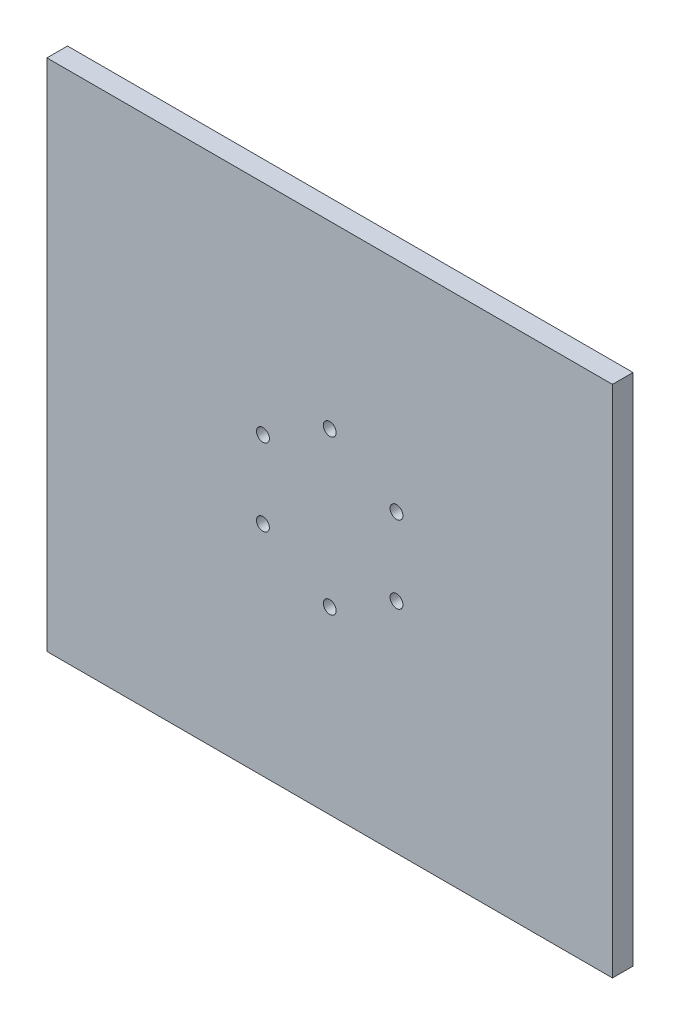
SolidWorks part; units mm, degrees
material "轻木"
ref_plane "前视基准面" through (0, 0, 0) normal (0, 0, 1) x (1, 0, 0)
ref_plane "上视基准面" through (0, 0, 0) normal (0, 1, 0) x (1, 0, 0)
ref_plane "右视基准面" through (0, 0, 0) normal (1, 0, 0) x (0, 0, -1)
sketch "草图1" plane through (0, 0, 0) normal (0, 0, 1) x (1, 0, 0)
  line L1 (0, 0) -> (220, 0)
  line L2 (0, 0) -> (0, -200)
  line L3 (0, -200) -> (220, -200)
  line L4 (220, 0) -> (220, -200)
  dimension "D1" = 200
  dimension "D2" = 220
extrude "凸台-拉伸1" add sketch "草图1" along normal blind 8
sketch "草图2" plane through (0, 0, 8) normal (0, 0, 1) x (1, 0, 0)
  line L0 (220, -200) -> (0, 0) construction
  line L1 (110, -100) -> (110, -70) construction
  line L2 (0, -200) -> (220, 0) construction
  circle A0 centre (110, -70) radius 2.5
  circle A1 centre (110, -100) radius 30 construction
  circle A2 centre (135.9808, -85) radius 2.5
  circle A3 centre (135.9808, -115) radius 2.5
  circle A4 centre (110, -130) radius 2.5
  circle A5 centre (84.0192, -115) radius 2.5
  circle A6 centre (84.0192, -85) radius 2.5
  dimension "D2" = 5
  dimension "D1" = 30
  dimension "D3" = 6
extrude "切除-拉伸1" cut sketch "草图2" against normal through all
